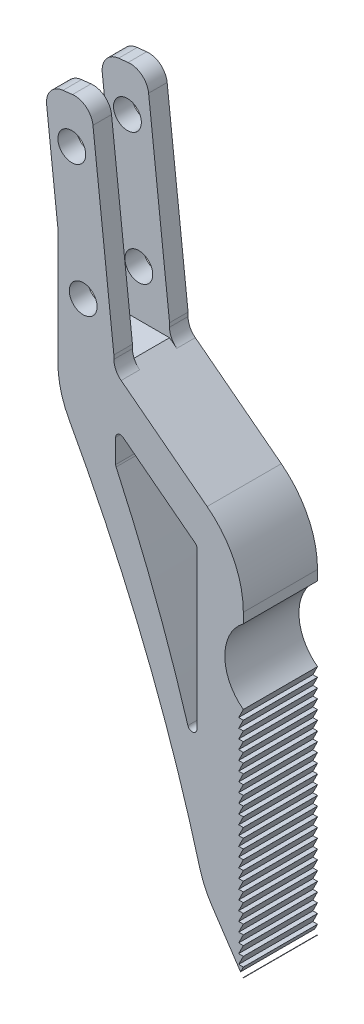
SolidWorks part; units mm, degrees
ref_plane "Front Plane" through (0, 0, 0) normal (0, 0, 1) x (1, 0, 0)
ref_plane "Top Plane" through (0, 0, 0) normal (0, 1, 0) x (1, 0, 0)
ref_plane "Right Plane" through (0, 0, 0) normal (1, 0, 0) x (0, 0, -1)
sketch "Sketch1" plane through (0, 0, 0) normal (0, 0, 1) x (1, 0, 0)
  line L0 (0, 0) -> (-20, 29.9333)
  line L1 (-20, 29.9333) -> (-20, 60.0633)
  line L2 (-20, 60.0633) -> (-21.4356, 72.9838)
  line L3 (-21.4356, 72.9838) -> (-16.4356, 73.5393)
  line L4 (-16.4356, 73.5393) -> (-13.9579, 51.2393)
  line L5 (-13.9579, 51.2393) -> (-13.9579, 49.8393)
  line L6 (-13.9579, 49.8393) -> (0, 39.1013)
  line L7 (0, 39.1013) -> (0, 0)
  dimension "D1" = 20
  dimension "D2" = 36
  dimension "D3" = 30.13
  dimension "D4" = 13
  dimension "D5" = 186.34
  dimension "D6" = 5
  dimension "D7" = 22.3
  dimension "D8" = 1.4
  dimension "D9" = 173.66
  dimension "D10" = 17.6104
  dimension "D11" = 127.572
  dimension "D12" = 10.738
extrude "Boss-Extrude1" add sketch "Sketch1" along normal mid plane 8
sketch "Sketch2" plane through (0, 0, 0) normal (0, 0, 1) x (1, 0, 0)
  line L1 (-13.9579, 49.8393) -> (-33.9579, 49.8393)
  line L2 (-13.9579, 49.8393) -> (-13.9579, 74.8393)
  line L3 (-13.9579, 74.8393) -> (-33.9579, 74.8393)
  line L4 (-33.9579, 49.8393) -> (-33.9579, 74.8393)
  dimension "D1" = 20
  dimension "D2" = 25
extrude "Cut-Extrude1" cut sketch "Sketch2" against normal mid plane 4
sketch "Sketch3" plane through (0, 0, 4) normal (0, 0, 1) x (1, 0, 0)
  line L0 (0, 0) -> (0, 39.1013) construction
  arc A0 (0, 33.1013) -> (0, 25.1013) centre (3, 29.1013) ccw
  dimension "D1" = 5
  dimension "D2" = 6
  dimension "D3" = 10
extrude "Cut-Extrude2" cut sketch "Sketch3" against normal through all and the other way through all
sketch "Sketch5" plane through (0, 0, 4) normal (0, 0, 1) x (1, 0, 0)
  line L0 (0, 25.1013) -> (-0.5, 24.1013)
  line L1 (-0.5, 24.1013) -> (0, 24.1013)
  line L2 (0, 0) -> (0, 25.1013) construction
  line L3 (0, 24.1013) -> (0, 25.1013)
  dimension "D1" = 1
  dimension "D2" = 0.5
extrude "Cut-Extrude3" cut sketch "Sketch5" against normal through all
pattern_linear "LPattern1" count 26 spacing 1.0025 along (0, -1, 0) of "Cut-Extrude3"
sketch "Sketch6" plane through (0, 0, 4) normal (0, 0, 1) x (1, 0, 0)
  line L0 (-20, 60.0633) -> (-20, 29.9333) construction
  line L1 (-20, 29.9333) -> (-0.2978, 0.4457) construction
  line L2 (-20, 44.9333) -> (-20, 29.9333)
  line L3 (-20, 29.9333) -> (-4.285, 6.4133)
  arc A0 (-20, 44.9333) -> (-4.285, 6.4133) centre (-159.0309, -34.2526) cw
  dimension "D3" = 160
  dimension "D1" = 15
  dimension "D2" = 23.52
extrude "Cut-Extrude4" cut sketch "Sketch6" against normal through all
sketch "Sketch7" plane through (0, 0, 4) normal (0, 0, 1) x (1, 0, 0)
  line L0 (-13.7661, 44.645) -> (-5, 37.9011)
  line L1 (-5, 37.9011) -> (-5, 17.285)
  line L2 (0, 33.1013) -> (0, 39.1013) construction
  line L3 (0, 39.1013) -> (-13.9579, 49.8393) construction
  line L4 (-13.7661, 44.645) -> (-13.7661, 40.985)
  arc A0 (-13.7661, 40.985) -> (-5, 17.285) centre (-158.9784, -26.1967) cw
  dimension "D6" = 160
  dimension "D1" = 4
  dimension "D2" = 5
  dimension "D3" = 3.66
  dimension "D4" = 23.7
  dimension "D5" = 11.06
extrude "Cut-Extrude5" cut sketch "Sketch7" against normal through all
fillet "Fillet1" radius 10 3 edges at (-20, 44.9333, 0) (-4.285, 6.4133, 0) (0, 39.1013, 0)
fillet "Fillet2" radius 2 6 edges at (-13.9579, 49.8393, -3) (-13.9579, 49.8393, 3) (-16.4356, 73.5393, -3) (-21.4356, 72.9838, -3) (-16.4356, 73.5393, 3) (-21.4356, 72.9838, 3)
fillet "Fillet3" radius 0.5 4 edges at (-5, 17.285, 0) (-13.7661, 44.645, 0) (-5, 37.9011, 0) (-13.7661, 40.985, 0)
sketch "Sketch8" plane through (0, 0, 4) normal (0, 0, 1) x (1, 0, 0)
  line L2 (-18.9356, 73.2615) -> (-17.2695, 54.8315) construction
  line L3 (-18.4233, 73.3184) -> (-19.4478, 73.2046) construction
  circle A0 centre (-18.498, 68.4215) radius 1.5
  circle A2 centre (-17.2695, 54.8315) radius 1.5
  dimension "D1" = 3
  dimension "D2" = 3
  dimension "D3" = 4.84
  dimension "D4" = 18.43
extrude "Cut-Extrude6" cut sketch "Sketch8" against normal through all
